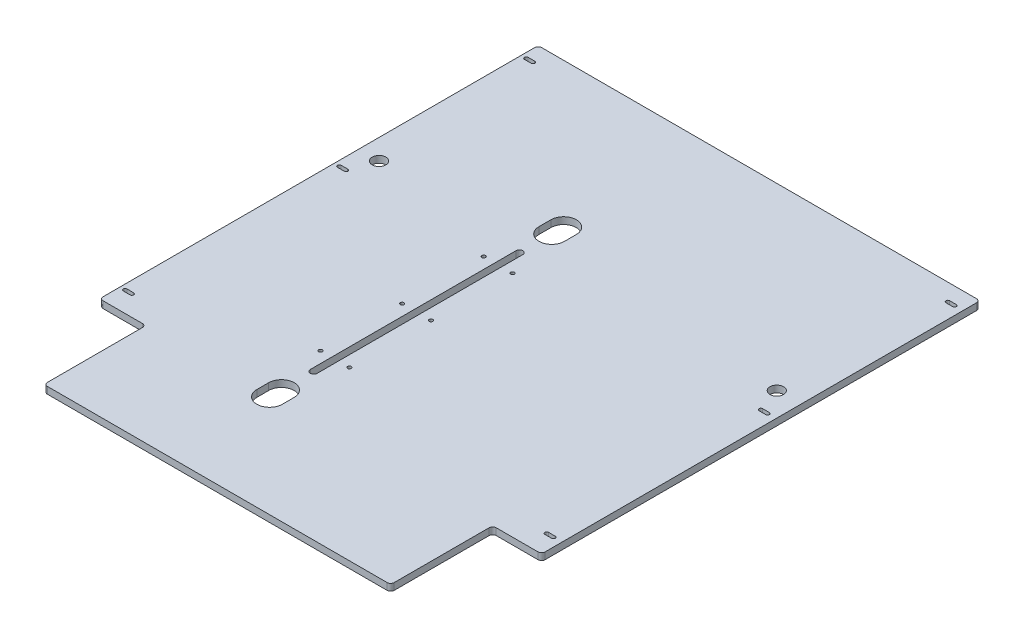
SolidWorks part; units mm, degrees
material "PE High Density"
ref_plane "Front" through (0, 0, 0) normal (0, 0, 1) x (1, 0, 0)
ref_plane "Top" through (0, 0, 0) normal (0, 1, 0) x (1, 0, 0)
ref_plane "Right" through (0, 0, 0) normal (1, 0, 0) x (0, 0, -1)
sketch "Sketch1" plane through (0, 0, 0) normal (0, 1, 0) x (1, 0, 0)
  line L0 (0, 0) -> (96.0438, 0)
  line L1 (96.0438, 0) -> (96.0438, -190.5)
  line L2 (96.0438, -190.5) -> (743.7437, -190.5)
  line L3 (743.7437, -190.5) -> (743.7437, 0)
  line L4 (743.7437, 0) -> (838.2, 0)
  line L5 (838.2, 0) -> (838.2, 819.15)
  line L6 (838.2, 819.15) -> (0, 819.15)
  line L7 (0, 819.15) -> (0, 0)
  line L8 (25.4, 0) -> (25.4, 819.15) construction
  line L9 (19.05, 38.1) -> (31.75, 38.1) construction
  line L10 (19.05, 41.4782) -> (31.75, 41.4782)
  line L11 (19.05, 34.7218) -> (31.75, 34.7218)
  line L12 (19.05, 438.15) -> (31.75, 438.15) construction
  line L13 (19.05, 441.5282) -> (31.75, 441.5282)
  line L14 (19.05, 434.7718) -> (31.75, 434.7718)
  line L15 (31.75, 787.4) -> (19.05, 787.4) construction
  line L16 (31.75, 784.0218) -> (19.05, 784.0218)
  line L17 (31.75, 790.7782) -> (19.05, 790.7782)
  line L18 (419.8937, 819.15) -> (419.8938, -190.5) construction
  line L19 (812.8, 787.4) -> (812.8, 438.15) construction
  line L20 (806.45, 787.4) -> (819.15, 787.4) construction
  line L21 (806.45, 784.0218) -> (819.15, 784.0218)
  line L22 (806.45, 790.7782) -> (819.15, 790.7782)
  line L23 (819.15, 438.15) -> (806.45, 438.15) construction
  line L24 (819.15, 441.5282) -> (806.45, 441.5282)
  line L25 (819.15, 434.7718) -> (806.45, 434.7718)
  line L26 (819.15, 38.1) -> (806.45, 38.1) construction
  line L27 (819.15, 41.4782) -> (806.45, 41.4782)
  line L28 (819.15, 34.7218) -> (806.45, 34.7218)
  line L29 (419.8938, -190.5) -> (419.8937, 819.15) construction
  line L30 (812.8, 438.15) -> (812.8, 38.1) construction
  arc A1 (19.05, 41.4782) -> (19.05, 34.7218) centre (19.05, 38.1) ccw
  arc A2 (31.75, 34.7218) -> (31.75, 41.4782) centre (31.75, 38.1) ccw
  arc A3 (19.05, 441.5282) -> (19.05, 434.7718) centre (19.05, 438.15) ccw
  arc A4 (31.75, 434.7718) -> (31.75, 441.5282) centre (31.75, 438.15) ccw
  arc A5 (31.75, 784.0218) -> (31.75, 790.7782) centre (31.75, 787.4) ccw
  arc A6 (19.05, 790.7782) -> (19.05, 784.0218) centre (19.05, 787.4) ccw
  arc A7 (806.45, 784.0218) -> (806.45, 790.7782) centre (806.45, 787.4) cw
  arc A8 (819.15, 790.7782) -> (819.15, 784.0218) centre (819.15, 787.4) cw
  arc A9 (819.15, 441.5282) -> (819.15, 434.7718) centre (819.15, 438.15) cw
  arc A10 (806.45, 434.7718) -> (806.45, 441.5282) centre (806.45, 438.15) cw
  arc A11 (819.15, 41.4782) -> (819.15, 34.7218) centre (819.15, 38.1) cw
  arc A12 (806.45, 34.7218) -> (806.45, 41.4782) centre (806.45, 38.1) cw
  point P13 (25.4, 38.1)
  point P20 (25.4, 438.15)
  point P27 (25.4, 787.4)
  point P38 (812.8, 787.4)
  point P45 (812.8, 438.15)
  point P52 (812.8, 38.1)
  dimension "D2" = 96.0438
  dimension "D3" = 819.15
  dimension "D4" = 25.4
  dimension "D5" = 6.7564
  dimension "D6" = 38.1
  dimension "D7" = 12.7
  dimension "D8" = 400.05
  dimension "D9" = 349.25
  dimension "D10" = 190.5
  dimension "D11" = 647.7
  dimension "D12" = 25.4
  dimension "D13" = 94.4562
extrude "Boss-Extrude1" add sketch "Sketch1" along normal blind 12.7
fillet "Fillet1" radius 6.604 2 edges at (96.0438, 6.35, 0) (743.7437, 6.35, 0)
fillet "Fillet2" radius 6.604 6 edges at (0, 6.35, -819.15) (838.2, 6.35, -819.15) (838.2, 6.35, 0) (743.7437, 6.35, 190.5) (0, 6.35, 0) (96.0438, 6.35, 190.5)
sketch "Sketch2" plane through (0, 12.7, 0) normal (0, 1, 0) x (1, 0, 0)
  line L0 (838.2, 6.604) -> (838.2, 812.546) construction
  line L1 (838.2, 6.604) -> (838.2, 812.546) construction
  line L3 (806.45, 438.15) -> (819.15, 438.15) construction
  line L5 (838.2, 483.87) -> (47.625, 483.87) construction
  line L6 (0, 812.546) -> (0, 6.604) construction
  circle A6 centre (47.625, 483.87) radius 12.7
  circle A7 centre (790.575, 483.87) radius 12.7
  dimension "D1" = 45.72
  dimension "D2" = 25.4
  dimension "D3" = 47.625
  dimension "D4" = 47.625
extrude "Cut-Extrude1" cut sketch "Sketch2" against normal through all
sketch "Sketch4" plane through (0, 0, 0) normal (0, -1, 0) x (1, 0, 0)
  line L0 (0, -812.546) -> (0, -6.604) construction
  line L3 (327.025, -527.05) -> (327.025, -549.275) construction
  line L4 (350.8375, -527.05) -> (350.8375, -549.275)
  line L5 (303.2125, -527.05) -> (303.2125, -549.275)
  line L7 (831.596, -819.15) -> (6.604, -819.15) construction
  line L8 (327.025, 0) -> (327.025, -22.225) construction
  line L9 (350.8375, 0) -> (350.8375, -22.225)
  line L10 (303.2125, 0) -> (303.2125, -22.225)
  circle A0 centre (327.025, -538.1625) radius 28.575 construction
  arc A2 (350.8375, -527.05) -> (303.2125, -527.05) centre (327.025, -527.05) ccw
  arc A3 (303.2125, -549.275) -> (350.8375, -549.275) centre (327.025, -549.275) ccw
  arc A4 (350.8375, 0) -> (303.2125, 0) centre (327.025, 0) ccw
  arc A5 (303.2125, -22.225) -> (350.8375, -22.225) centre (327.025, -22.225) ccw
  point P8 (327.025, -11.1125)
  point P12 (327.025, -538.1625)
  dimension "D2" = 57.15
  dimension "D1" = 327.025
  dimension "D3" = 527.05
  dimension "D4" = 47.625
  dimension "D5" = 22.225
  dimension "D6" = 280.9875
extrude "Cut-Extrude3" cut sketch "Sketch4" against normal through all
sketch "Sketch5" plane through (0, 0, 0) normal (0, -1, 0) x (1, 0, 0)
  line L0 (327.025, -22.225) -> (327.025, -527.05) construction
  line L1 (327.025, -466.725) -> (327.025, -82.55) construction
  line L2 (320.675, -466.725) -> (320.675, -82.55)
  line L3 (333.375, -466.725) -> (333.375, -82.55)
  arc A0 (320.675, -466.725) -> (333.375, -466.725) centre (327.025, -466.725) ccw
  arc A1 (333.375, -82.55) -> (320.675, -82.55) centre (327.025, -82.55) ccw
  point P6 (327.025, -274.6375)
  dimension "D1" = 384.175
  dimension "D2" = 12.7
extrude "Cut-Extrude4" cut sketch "Sketch5" against normal through all
sketch "Sketch6" plane through (0, 0, 0) normal (0, -1, 0) x (1, 0, 0)
  line L0 (327.025, -82.55) -> (327.025, -466.725) construction
  line L1 (327.025, -274.6375) -> (354.0125, -274.6375) construction
  line L2 (354.0125, -122.2375) -> (354.0125, -427.0375) construction
  line L3 (300.0375, -122.2375) -> (300.0375, -427.0375) construction
  circle A0 centre (354.0125, -274.6375) radius 3.3782
  circle A1 centre (354.0125, -427.0375) radius 3.3782
  circle A2 centre (354.0125, -122.2375) radius 3.3782
  circle A3 centre (300.0375, -427.0375) radius 3.3782
  circle A4 centre (300.0375, -274.6375) radius 3.3782
  circle A5 centre (300.0375, -122.2375) radius 3.3782
  dimension "D2" = 6.7564
  dimension "D1" = 26.9875
  dimension "D3" = 152.4
extrude "Cut-Extrude5" cut sketch "Sketch6" against normal through all
sketch "Sketch7" plane through (0, 0, 0) normal (0, -1, 0) x (1, 0, 0)
  line L0 (838.2, -6.604) -> (838.2, -812.546) construction
  line L1 (0, -812.546) -> (0, -6.604) construction
  line L2 (838.2, -6.604) -> (838.2, -812.546)
  line L3 (0, -812.546) -> (0, -6.604)
  line L4 (835.025, -6.604) -> (835.025, -812.546)
  line L5 (9.525, -812.546) -> (9.525, -6.604)
  line L6 (16.129, -819.15) -> (6.604, -819.15)
  line L7 (16.129, 0) -> (6.604, 0)
  line L8 (831.596, 0) -> (828.421, 0)
  line L9 (828.421, -819.15) -> (831.596, -819.15)
  arc A0 (838.2, -6.604) -> (831.596, 0) centre (831.596, -6.604) ccw construction
  arc A1 (831.596, -819.15) -> (838.2, -812.546) centre (831.596, -812.546) ccw construction
  arc A2 (0, -812.546) -> (6.604, -819.15) centre (6.604, -812.546) ccw construction
  arc A3 (6.604, 0) -> (0, -6.604) centre (6.604, -6.604) ccw construction
  arc A4 (838.2, -6.604) -> (831.596, 0) centre (831.596, -6.604) ccw
  arc A5 (831.596, -819.15) -> (838.2, -812.546) centre (831.596, -812.546) ccw
  arc A6 (0, -812.546) -> (6.604, -819.15) centre (6.604, -812.546) ccw
  arc A7 (6.604, 0) -> (0, -6.604) centre (6.604, -6.604) ccw
  arc A8 (835.025, -6.604) -> (828.421, 0) centre (828.421, -6.604) ccw
  arc A9 (828.421, -819.15) -> (835.025, -812.546) centre (828.421, -812.546) ccw
  arc A10 (16.129, 0) -> (9.525, -6.604) centre (16.129, -6.604) ccw
  arc A11 (9.525, -812.546) -> (16.129, -819.15) centre (16.129, -812.546) ccw
  dimension "D2" = 3.175
  dimension "D4" = 9.525
  dimension "D1" = 2
  dimension "D3" = 2
extrude "Cut-Extrude6" cut sketch "Sketch7" against normal through all contours A9 L9 A5 L2 A4 L8 A8 L4 | A11 L5 A10 L7 A7 L3 A6 L6
